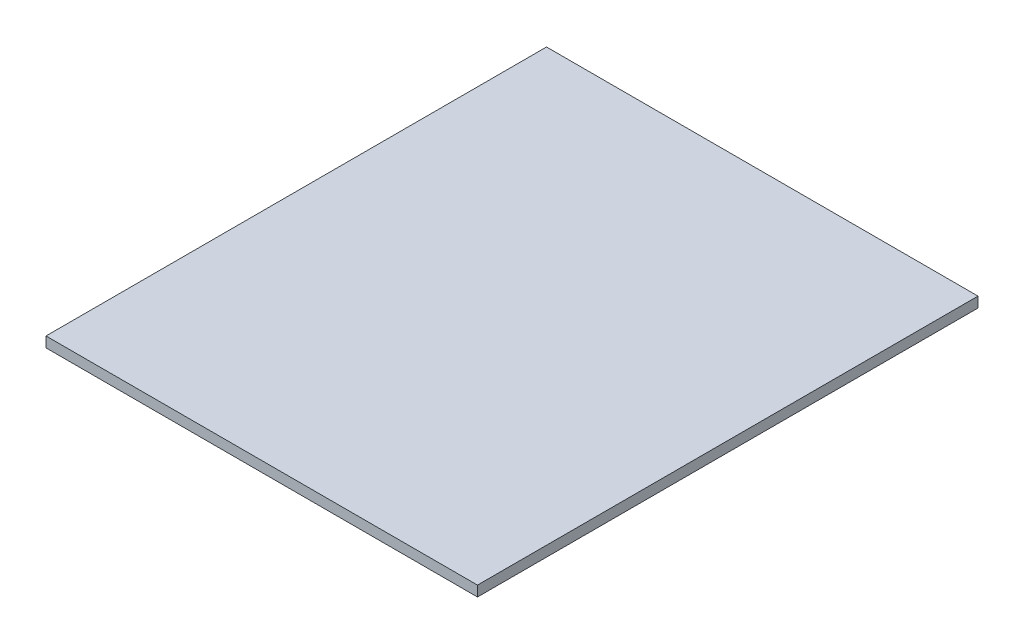
SolidWorks part; units mm, degrees
ref_plane "Plano frontal" through (0, 0, 0) normal (0, 0, 1) x (1, 0, 0)
ref_plane "Plano superior" through (0, 0, 0) normal (0, 1, 0) x (1, 0, 0)
ref_plane "Plano direito" through (0, 0, 0) normal (1, 0, 0) x (0, 0, -1)
sketch "Esboço1" plane through (0, 0, 0) normal (0, 1, 0) x (1, 0, 0)
  line L1 (0, 0) -> (238, 0)
  line L2 (0, 0) -> (0, 250)
  line L3 (0, 250) -> (238, 250)
  line L4 (238, 0) -> (238, 250)
extrude "Ressalto-extrusão1" add sketch "Esboço1" along normal blind 6
sketch "Esboço2" plane through (0, 0, 0) normal (-1, 0, 0) x (0, 0, 1)
  line L1 (0, 6) -> (-250, 6)
  line L2 (0, 6) -> (0, 0)
  line L3 (0, 0) -> (-250, 0)
  line L4 (-250, 6) -> (-250, 0)
extrude "Ressalto-extrusão2" add sketch "Esboço2" along normal blind 12
sketch "Esboço3" plane through (0, 0, -250) normal (0, 0, -1) x (-1, 0, 0)
  line L0 (12, 6) -> (12, 0) construction
  line L1 (-238, 6) -> (12, 6)
  line L2 (-238, 6) -> (-238, 0)
  line L3 (-238, 0) -> (12, 0)
  line L4 (12, 6) -> (12, 0)
  line L5 (-238, 0) -> (12, 0) construction
extrude "Ressalto-extrusão3" add sketch "Esboço3" along normal blind 40
